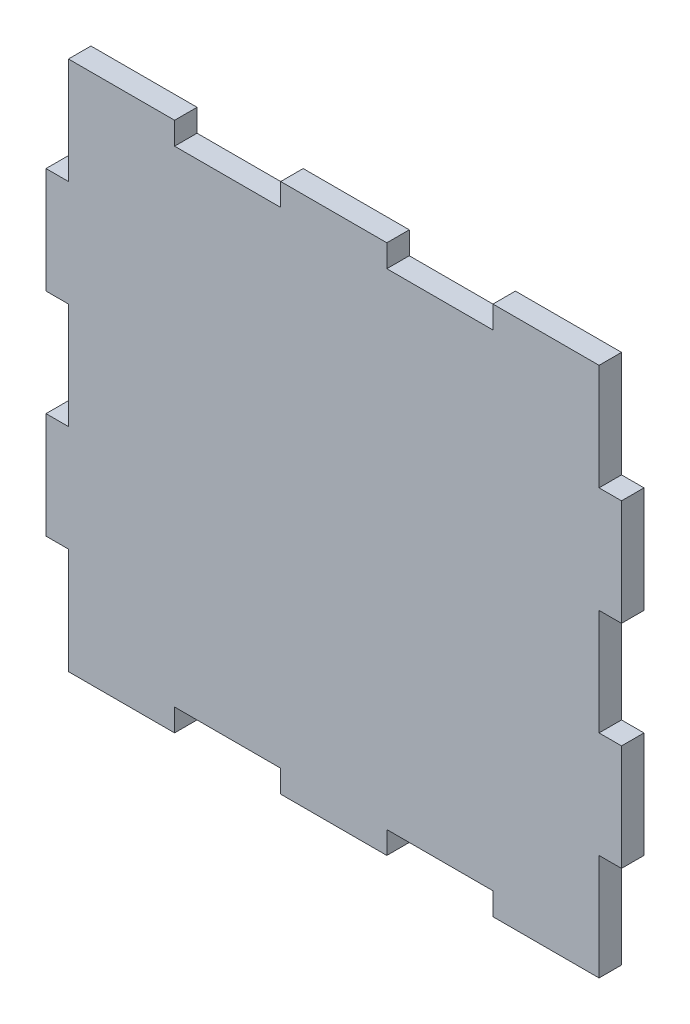
SolidWorks part; units mm, degrees
ref_plane "Front Plane" through (0, 0, 0) normal (0, 0, 1) x (1, 0, 0)
ref_plane "Top Plane" through (0, 0, 0) normal (0, 1, 0) x (1, 0, 0)
ref_plane "Right Plane" through (0, 0, 0) normal (1, 0, 0) x (0, 0, -1)
sketch "Sketch1" plane through (0, 0, 0) normal (0, 0, 1) x (1, 0, 0)
  line L0 (-197.4136, 80.5732) -> (-197.4136, 50.5732)
  line L1 (-197.4136, -39.4268) -> (-197.4136, -69.4268)
  line L2 (-47.4136, 80.5732) -> (-47.4136, 50.5732)
  line L3 (-197.4136, -69.4268) -> (-167.4136, -69.4268)
  line L4 (-197.4136, 80.5732) -> (-167.4136, 80.5732)
  line L5 (-197.4136, 50.5732) -> (-203.7636, 50.5732)
  line L6 (-203.7636, 50.5732) -> (-203.7636, 20.5732)
  line L7 (-203.7636, 20.5732) -> (-197.4136, 20.5732)
  line L8 (-197.4136, 20.5732) -> (-197.4136, -9.4268)
  line L9 (-197.4136, -9.4268) -> (-203.7636, -9.4268)
  line L10 (-203.7636, -9.4268) -> (-203.7636, -39.4268)
  line L11 (-203.7636, -39.4268) -> (-197.4136, -39.4268)
  line L12 (-167.4136, -69.4268) -> (-167.4136, -63.0768)
  line L13 (-47.4136, 50.5732) -> (-41.0636, 50.5732)
  line L14 (-41.0636, 50.5732) -> (-41.0636, 20.5732)
  line L15 (-41.0636, 20.5732) -> (-47.4136, 20.5732)
  line L16 (-47.4136, 20.5732) -> (-47.4136, -9.4268)
  line L17 (-47.4136, -9.4268) -> (-41.0636, -9.4268)
  line L18 (-41.0636, -9.4268) -> (-41.0636, -39.4268)
  line L20 (-167.4136, -63.0768) -> (-137.4136, -63.0768)
  line L21 (-167.4136, 80.5732) -> (-167.4136, 74.2232)
  line L22 (-167.4136, 74.2232) -> (-137.4136, 74.2232)
  line L23 (-137.4136, 74.2232) -> (-137.4136, 80.5732)
  line L24 (-137.4136, 80.5732) -> (-107.4136, 80.5732)
  line L25 (-107.4136, 80.5732) -> (-107.4136, 74.2232)
  line L26 (-107.4136, 74.2232) -> (-77.4136, 74.2232)
  line L27 (-77.4136, 74.2232) -> (-77.4136, 80.5732)
  line L28 (-77.4136, 80.5732) -> (-47.4136, 80.5732)
  line L29 (-137.4136, -63.0768) -> (-137.4136, -69.4268)
  line L30 (-137.4136, -69.4268) -> (-107.4136, -69.4268)
  line L31 (-107.4136, -69.4268) -> (-107.4136, -63.0768)
  line L32 (-107.4136, -63.0768) -> (-77.4136, -63.0768)
  line L33 (-77.4136, -63.0768) -> (-77.4136, -69.4268)
  line L34 (-77.4136, -69.4268) -> (-47.4136, -69.4268)
  line L35 (-41.0636, -39.4268) -> (-47.4136, -39.4268)
  line L36 (-47.4136, -39.4268) -> (-47.4136, -69.4268)
  dimension "D2" = 30
  dimension "D3" = 30
  dimension "D4" = 30
  dimension "D5" = 30
  dimension "D6" = 30
  dimension "D7" = 6.35
  dimension "D8" = 30
  dimension "D9" = 30
  dimension "D10" = 30
  dimension "D11" = 30
  dimension "D12" = 30
  dimension "D13" = 6.35
  dimension "D14" = 6.35
  dimension "D15" = 6.35
  dimension "D16" = 6.35
extrude "Boss-Extrude1" add sketch "Sketch1" along normal blind 6.35
